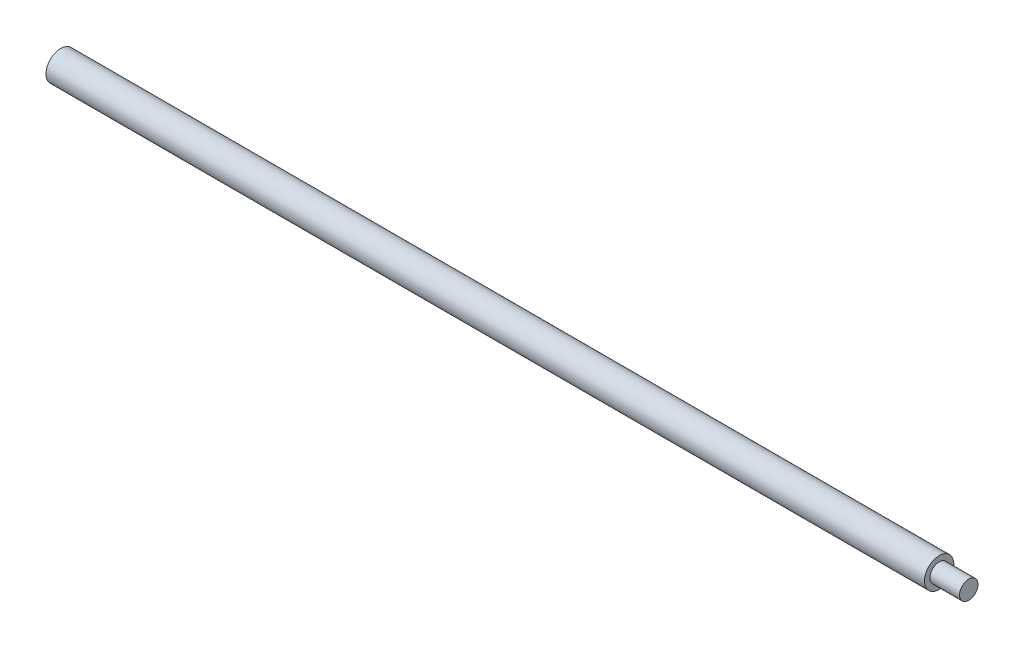
SolidWorks part; units mm, degrees
ref_plane "Front Plane" through (0, 0, 0) normal (0, 0, 1) x (1, 0, 0)
ref_plane "Top Plane" through (0, 0, 0) normal (0, 1, 0) x (1, 0, 0)
ref_plane "Right Plane" through (0, 0, 0) normal (1, 0, 0) x (0, 0, -1)
sketch "Sketch1" plane through (0, 0, 0) normal (1, 0, 0) x (0, 0, -1)
  circle A0 centre (0, 0) radius 3.175
  dimension "D1" = 6.35
extrude "Boss-Extrude1" add sketch "Sketch1" along normal mid plane 190
sketch "Sketch2" plane through (95, 0, 0) normal (1, 0, 0) x (0, 0, -1)
  circle A0 centre (0, 0) radius 2
  dimension "D1" = 4
extrude "Boss-Extrude2" add sketch "Sketch2" along normal blind 6.4
